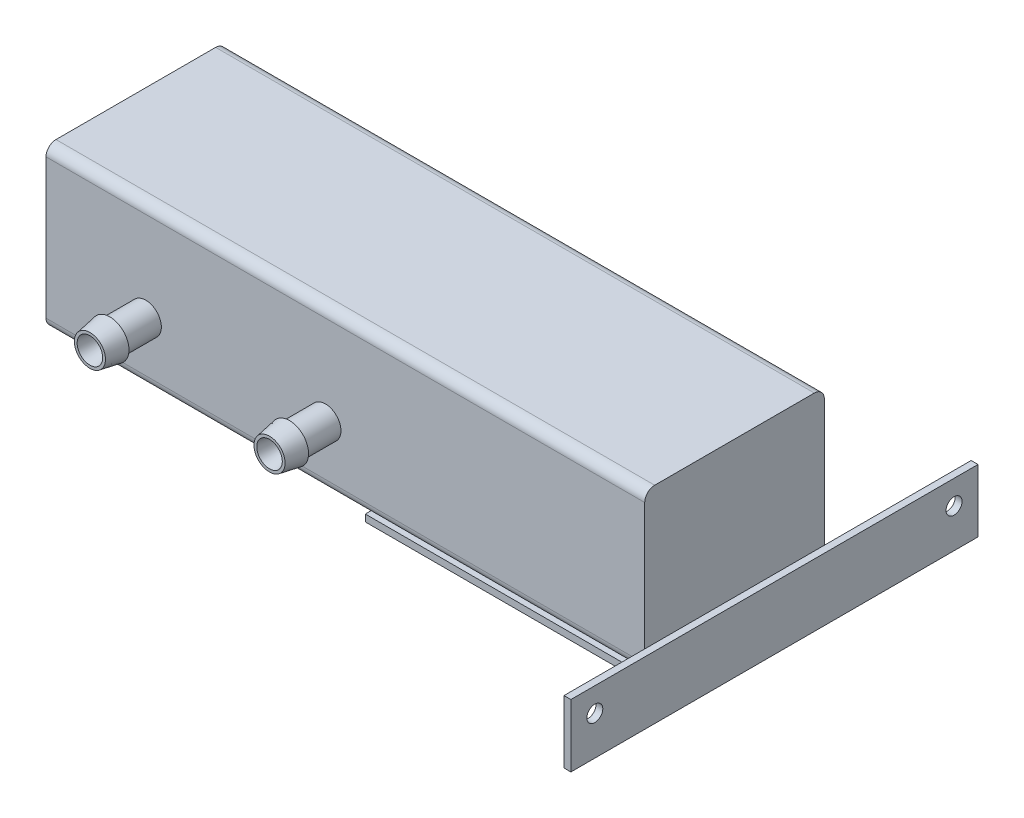
SolidWorks part; units mm, degrees
material "Rubber"
ref_plane "Front" through (0, 0, 0) normal (0, 0, 1) x (1, 0, 0)
ref_plane "Top" through (0, 0, 0) normal (0, 1, 0) x (1, 0, 0)
ref_plane "Right" through (0, 0, 0) normal (1, 0, 0) x (0, 0, -1)
sketch "Sketch1" plane through (0, 0, 0) normal (0, 0, 1) x (1, 0, 0)
  line L0 (52.5, 97.6) -> (52.5, -7.4) construction
  line L1 (-95.25, 25.4) -> (95.25, 25.4)
  line L2 (-95.25, 25.4) -> (-95.25, -25.4)
  line L3 (-95.25, -25.4) -> (95.25, -25.4)
  line L4 (95.25, 25.4) -> (95.25, -25.4)
  line L5 (-95.25, 25.4) -> (95.25, -25.4) construction
  line L6 (-95.25, -25.4) -> (95.25, 25.4) construction
  line L7 (52.5, -7.4) -> (-52.5, -7.4) construction
  line L9 (52.5, 97.6) -> (-52.5, 97.6) construction
  line L11 (-52.5, -7.4) -> (-52.5, 97.6) construction
  line L12 (-52.5, 45.1) -> (-95.25, 45.1) construction
  line L13 (52.5, 45.1) -> (95.25, 45.1) construction
  circle A0 centre (-52.5, 97.6) radius 1.5875 construction
  circle A1 centre (52.5, 97.6) radius 1.5875 construction
  circle A2 centre (52.5, -7.4) radius 1.5875 construction
  circle A3 centre (-52.5, -7.4) radius 1.5875 construction
  point P0 (0, 0)
  point P6 (0, 0)
  dimension "D3" = 3.175
  dimension "D1" = 50.8
  dimension "D2" = 190.5
  dimension "D4" = 105
  dimension "D5" = 105
  dimension "D6" = 18
extrude "Boss-Extrude1" add sketch "Sketch1" along normal mid plane 57.15
sketch "Sketch2" plane through (0, 0, 28.575) normal (0, 0, 1) x (1, 0, 0)
  line L0 (-63.5, -6.35) -> (-6.35, -6.35) construction
  line L1 (-95.25, 25.4) -> (-95.25, -25.4) construction
  line L2 (95.25, 25.4) -> (-95.25, 25.4) construction
  circle A0 centre (-63.5, -6.35) radius 4.953
  circle A1 centre (-6.35, -6.35) radius 4.953
  circle A2 centre (-63.5, -6.35) radius 4.064
  circle A3 centre (-6.35, -6.35) radius 4.064
  dimension "D1" = 9.906
  dimension "D4" = 8.128
  dimension "D2" = 57.15
  dimension "D3" = 31.75
  dimension "D5" = 31.75
  dimension "D6" = 31.75
extrude "Boss-Extrude2" add sketch "Sketch2" along normal blind 17.78
sketch "Sketch3" plane through (0, 0, 46.355) normal (0, 0, 1) x (1, 0, 0)
  circle A0 centre (-63.5, -6.35) radius 4.064 construction
  circle A1 centre (-63.5, -6.35) radius 4.953
  circle A2 centre (-63.5, -6.35) radius 4.953
  circle A3 centre (-6.35, -6.35) radius 4.953
  circle A4 centre (-6.35, -6.35) radius 4.953
  circle A5 centre (-63.5, -6.35) radius 4.064
  circle A6 centre (-6.35, -6.35) radius 4.064 construction
  circle A7 centre (-6.35, -6.35) radius 4.064
  dimension "D1" = 0
  dimension "D2" = 0
extrude "Boss-Extrude3" add sketch "Sketch3" against normal blind 6.35 draft 10 draft outward yes
sketch "Sketch5" plane through (0, 0, 28.575) normal (0, 0, 1) x (1, 0, 0)
  line L0 (-95.25, -25.4) -> (95.25, -25.4) construction
  line L1 (6.35, -25.4) -> (105.7614, -25.4)
  line L2 (6.35, -25.4) -> (6.35, -27.5886)
  line L3 (6.35, -27.5886) -> (107.95, -27.5886)
  line L4 (107.95, -25.4) -> (107.95, -27.5886)
  line L5 (95.25, -25.4) -> (95.25, 25.4) construction
  line L6 (107.95, -25.4) -> (107.95, -7.62)
  line L7 (107.95, -7.62) -> (105.7614, -7.62)
  line L8 (105.7614, -7.62) -> (105.7614, -25.4)
  dimension "D1" = 2.1886
  dimension "D2" = 88.9
  dimension "D3" = 12.7
  dimension "D4" = 17.78
extrude "Boss-Extrude4" add sketch "Sketch5" against normal up to surface (57.15 mm away) separate body up to face at (0, 0, -28.575)
sketch "Sketch7" plane through (0, 0, 0) normal (0, 0, 1) x (1, 0, 0)
  line L1 (107.95, -27.5886) -> (105.7614, -27.5886)
  line L2 (107.95, -27.5886) -> (107.95, -7.62)
  line L3 (107.95, -7.62) -> (105.7614, -7.62)
  line L4 (105.7614, -27.5886) -> (105.7614, -7.62)
extrude "Boss-Extrude5" add sketch "Sketch7" along normal mid plane 129.54
sketch "Sketch8" plane through (105.7614, 0, 0) normal (-1, 0, 0) x (0, 0, 1)
  line L0 (0, 0) -> (0, -15.24) construction
  line L1 (0, -15.24) -> (57.15, -15.24) construction
  line L2 (0, -15.24) -> (-57.15, -15.24) construction
  line L3 (-64.77, -7.62) -> (64.77, -7.62) construction
  circle A0 centre (57.15, -15.24) radius 2.54
  circle A1 centre (-57.15, -15.24) radius 2.54
  dimension "D3" = 5.08
  dimension "D1" = 114.3
  dimension "D2" = 7.62
extrude "Cut-Extrude1" cut sketch "Sketch8" against normal through all
fillet "Fillet1" radius 3.175 4 edges at (0, 25.4, 28.575) (0, 25.4, -28.575) (0, -25.4, -28.575) (0, -25.4, 28.575)
